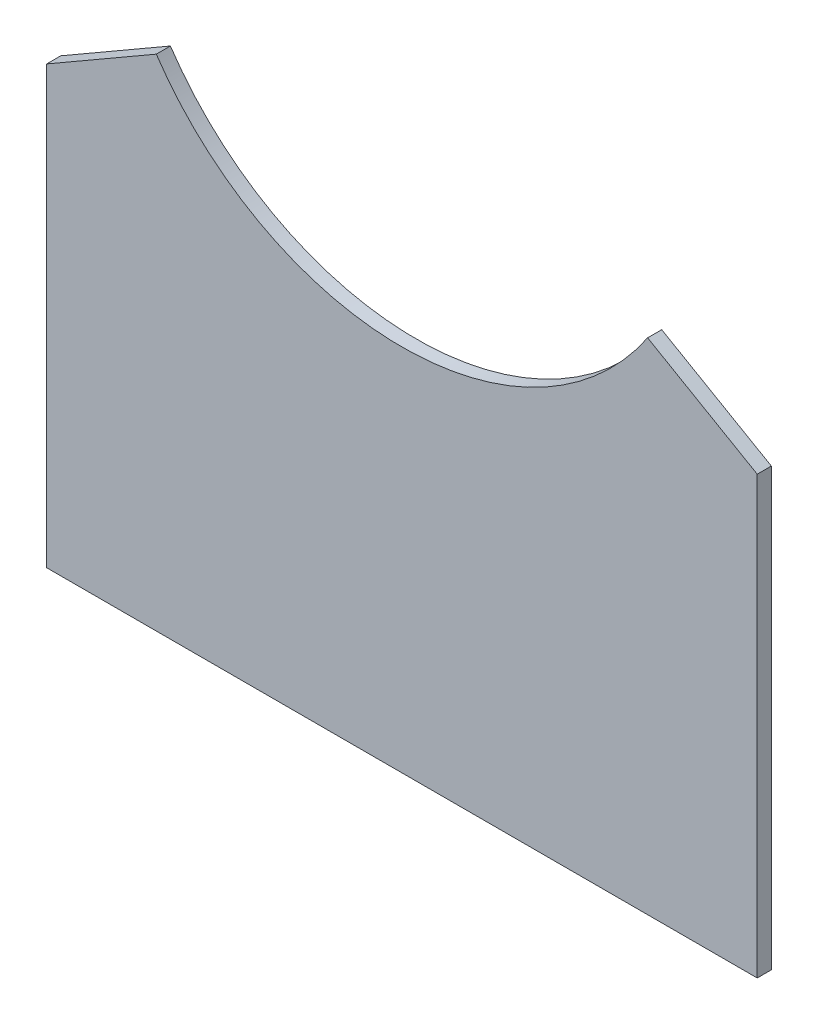
SolidWorks part; units mm, degrees
ref_plane "Front Plane" through (0, 0, 0) normal (0, 0, 1) x (1, 0, 0)
ref_plane "Top Plane" through (0, 0, 0) normal (0, 1, 0) x (1, 0, 0)
ref_plane "Right Plane" through (0, 0, 0) normal (1, 0, 0) x (0, 0, -1)
sketch "Sketch1" plane through (0, 0, 0) normal (0, 0, 1) x (1, 0, 0)
  line L0 (-221.2731, -148.8862) -> (-320, -205.8862)
  line L1 (-320, -205.8862) -> (-320, -598.8862)
  line L2 (-320, -598.8862) -> (320, -598.8862)
  line L3 (320, -598.8862) -> (320, -205.8862)
  line L4 (320, -205.8862) -> (221.2731, -148.8862)
  line L5 (0, 758.7969) -> (0, -1383.6885) construction
  arc A0 (-221.2731, -148.8862) -> (221.2731, -148.8862) centre (0, 0) ccw
  dimension "D2" = 266.7
  dimension "D6" = 60
  dimension "D1" = 60
  dimension "D3" = 393
  dimension "D4" = 640
  dimension "D5" = 450
extrude "Boss-Extrude1" add sketch "Sketch1" along normal mid plane 12.7
